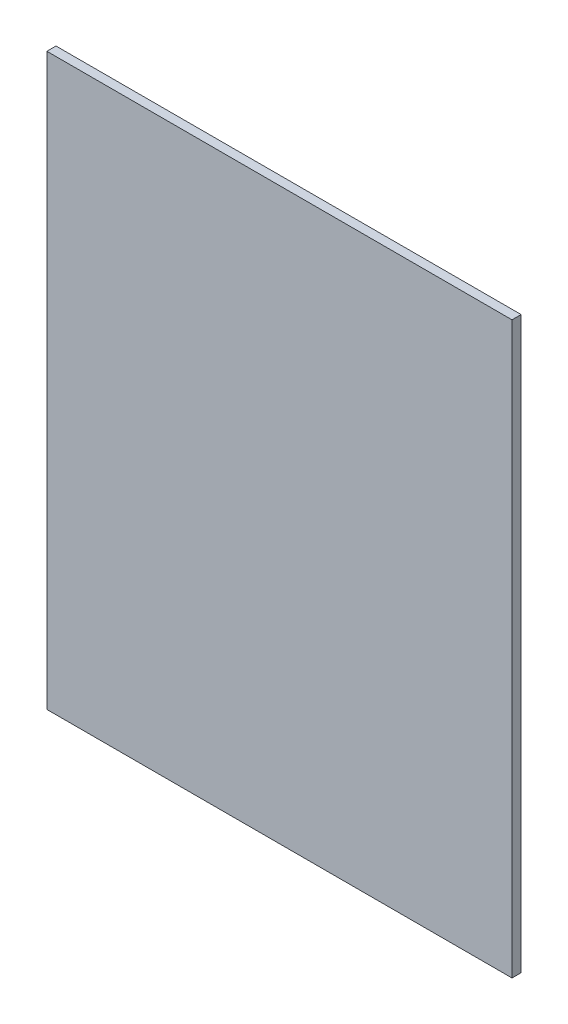
SolidWorks part; units mm, degrees
material "ABS PC"
ref_plane "Front Plane" through (0, 0, 0) normal (0, 0, 1) x (1, 0, 0)
ref_plane "Top Plane" through (0, 0, 0) normal (0, 1, 0) x (1, 0, 0)
ref_plane "Right Plane" through (0, 0, 0) normal (1, 0, 0) x (0, 0, -1)
sketch "Sketch1" plane through (0, 0, 0) normal (0, 0, 1) x (1, 0, 0)
  line L1 (-102, -125) -> (102, -125)
  line L2 (-102, -125) -> (-102, 125)
  line L3 (-102, 125) -> (102, 125)
  line L4 (102, -125) -> (102, 125)
  line L5 (-102, -125) -> (102, 125) construction
  line L6 (-102, 125) -> (102, -125) construction
  point P0 (0, 0)
  dimension "D1" = 204
  dimension "D2" = 250
extrude "Boss-Extrude1" add sketch "Sketch1" along normal blind 4
